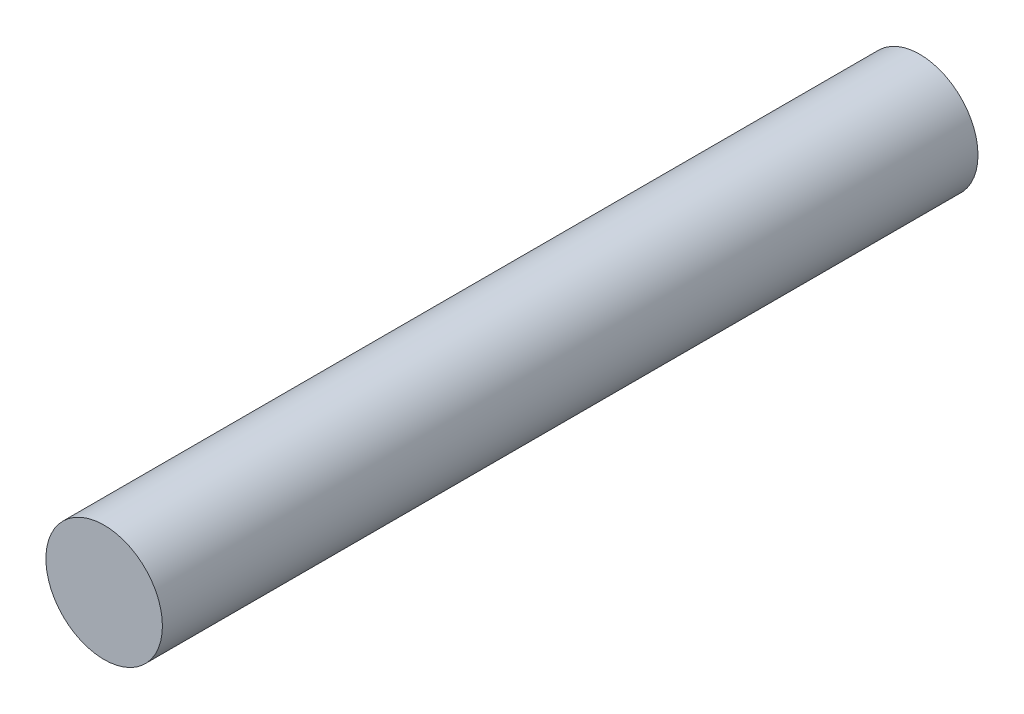
SolidWorks part; units mm, degrees
material "Aleación 1060"
ref_plane "Alzado" through (0, 0, 0) normal (0, 0, 1) x (1, 0, 0)
ref_plane "Planta" through (0, 0, 0) normal (0, 1, 0) x (1, 0, 0)
ref_plane "Vista lateral" through (0, 0, 0) normal (1, 0, 0) x (0, 0, -1)
sketch "Croquis1" plane through (0, 0, 0) normal (0, 0, 1) x (1, 0, 0)
  circle A0 centre (0, 0) radius 12.7
  dimension "D1" = 25.4
extrude "Saliente-Extruir1" add sketch "Croquis1" along normal blind 177.8
sketch "Croquis2" plane through (0, 0, 177.8) normal (0, 0, 1) x (1, 0, 0)
  line L0 (0, 0) -> (0, 12.7)
  circle A1 centre (0, 0) radius 12.7
  circle A2 centre (0, 0) radius 12.7
  point P1 (0, 0)
  dimension "D1" = 0
ref_plane "Plano1" through (0, 12.7, 177.8) normal (0, 1, 0) x (1, 0, 0)
